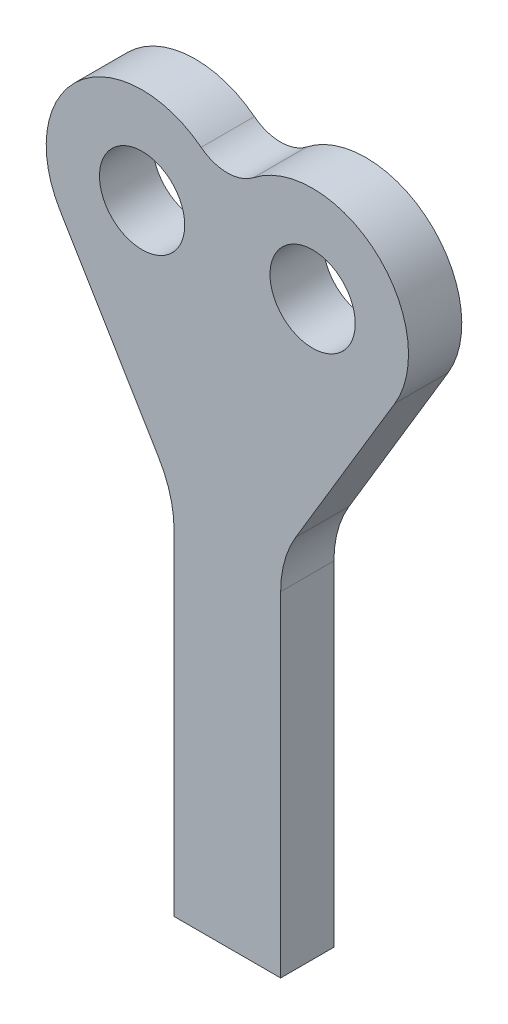
SolidWorks part; units mm, degrees
ref_plane "Front Plane" through (0, 0, 0) normal (0, 0, 1) x (1, 0, 0)
ref_plane "Top Plane" through (0, 0, 0) normal (0, 1, 0) x (1, 0, 0)
ref_plane "Right Plane" through (0, 0, 0) normal (1, 0, 0) x (0, 0, -1)
sketch "Sketch1" plane through (0, 0, 0) normal (0, 0, 1) x (1, 0, 0)
  line L0 (-5.08, 0) -> (5.08, 0) construction
  line L1 (0, 0) -> (0, -25.146) construction
  line L2 (-9.9823, -2.9375) -> (-4.078, -12.7911)
  line L3 (-11.303, -25.146) -> (11.303, -25.146) construction
  line L4 (-3.175, -35.9939) -> (3.175, -35.9939)
  line L5 (-3.175, -35.9939) -> (-3.175, -16.0549)
  line L7 (3.175, -35.9939) -> (3.175, -16.0549)
  line L8 (-3.175, -35.9939) -> (3.175, -14.2981) construction
  line L9 (-3.175, -14.2981) -> (3.175, -35.9939) construction
  line L10 (9.9823, -2.9375) -> (4.078, -12.7911)
  circle A0 centre (5.08, 0) radius 2.54
  circle A1 centre (-5.08, 0) radius 2.54
  arc A2 (11.303, -25.146) -> (3.175, -14.2981) centre (0, -25.146) ccw
  arc A3 (-1.5631, 4.5047) -> (-9.9823, -2.9375) centre (-5.08, 0) ccw
  arc A4 (9.9823, -2.9375) -> (1.5631, 4.5047) centre (5.08, 0) ccw
  arc A5 (1.5631, 4.5047) -> (-1.5631, 4.5047) centre (0, 6.5068) cw
  circle A6 centre (5.08, 0) radius 5.715 construction
  circle A7 centre (-5.08, 0) radius 5.715 construction
  arc A8 (-3.175, -14.2981) -> (-11.303, -25.146) centre (0, -25.146) ccw
  arc A9 (4.078, -12.7911) -> (3.175, -16.0549) centre (9.525, -16.0549) ccw
  arc A10 (-3.175, -16.0549) -> (-4.078, -12.7911) centre (-9.525, -16.0549) ccw
  point P4 (0, 0)
  point P13 (10.795, 0)
  point P16 (0.635, 0)
  point P24 (0, -25.146)
  point P28 (-3.175, -14.2981)
  point P29 (3.175, -14.7793)
  dimension "D2" = 5.08
  dimension "D3" = 25.146
  dimension "D4" = 22.606
  dimension "D8" = 6.35
  dimension "D1" = 10.16
  dimension "D7" = 6.35
  dimension "D5" = 3.175
extrude "Boss-Extrude1" add sketch "Sketch1" along normal blind 3.175
